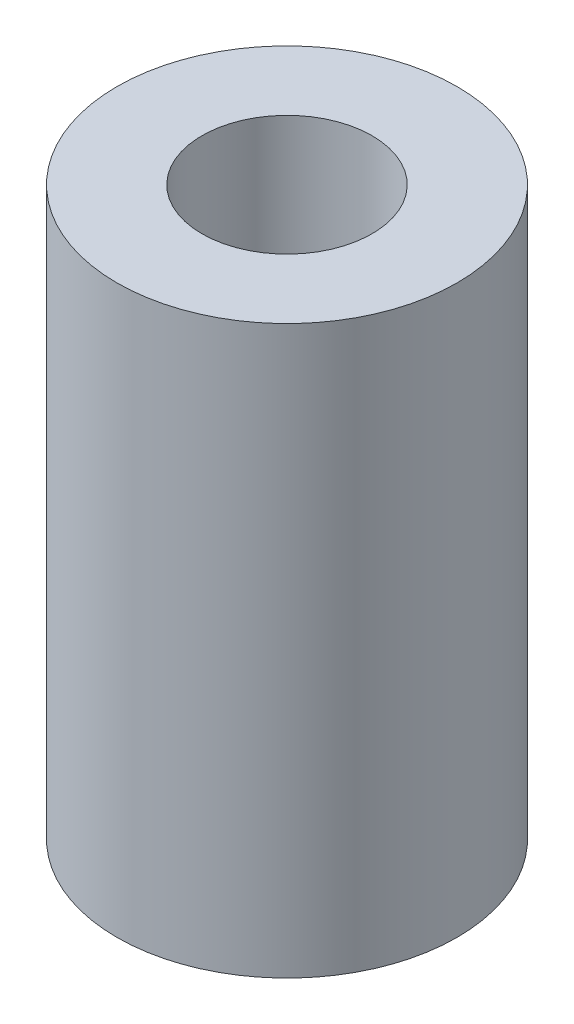
SolidWorks part; units mm, degrees
ref_plane "Front Plane" through (0, 0, 0) normal (0, 0, 1) x (1, 0, 0)
ref_plane "Top Plane" through (0, 0, 0) normal (0, 1, 0) x (1, 0, 0)
ref_plane "Right Plane" through (0, 0, 0) normal (1, 0, 0) x (0, 0, -1)
sketch "Sketch1" plane through (0, 0, 0) normal (0, 1, 0) x (1, 0, 0)
  circle A0 centre (0, 0) radius 3
  circle A1 centre (0, 0) radius 1.5
  dimension "D1" = 6
  dimension "D2" = 3
extrude "Boss-Extrude1" add sketch "Sketch1" along normal blind 10
